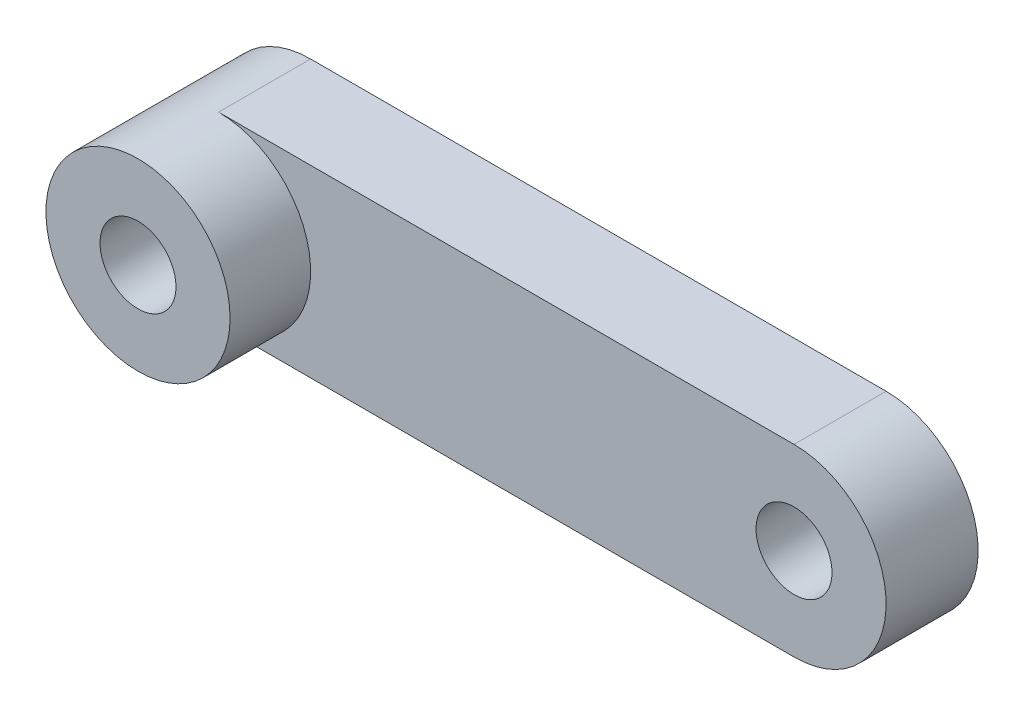
SolidWorks part; units mm, degrees
ref_plane "Front Plane" through (0, 0, 0) normal (0, 0, 1) x (1, 0, 0)
ref_plane "Top Plane" through (0, 0, 0) normal (0, 1, 0) x (1, 0, 0)
ref_plane "Right Plane" through (0, 0, 0) normal (1, 0, 0) x (0, 0, -1)
sketch "Sketch1" plane through (0, 0, 0) normal (0, 0, 1) x (1, 0, 0)
  line L0 (-25, 4) -> (0, 4)
  line L1 (-25, -4) -> (0, -4)
  arc A0 (0, -4) -> (0, 4) centre (0, 0) ccw
  circle A1 centre (0, 0) radius 1.65
  circle A2 centre (-25, 0) radius 1.65
  arc A3 (-25, 4) -> (-25, -4) centre (-25, 0) ccw
  dimension "D1" = 8
  dimension "D2" = 3.3
  dimension "D3" = 25
extrude "Boss-Extrude1" add sketch "Sketch1" along normal blind 4
sketch "Sketch2" plane through (0, 0, 4) normal (0, 0, 1) x (1, 0, 0)
  circle A0 centre (-25, 0) radius 4
  circle A1 centre (-25, 0) radius 1.65
  dimension "D1" = 3.3
  dimension "D2" = 8
extrude "Boss-Extrude2" add sketch "Sketch2" along normal blind 3.5
